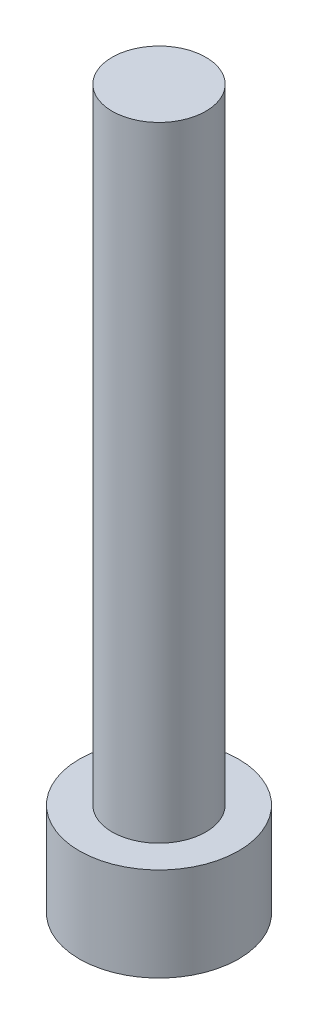
SolidWorks part; units mm, degrees
material "不锈钢 (铁素体)"
ref_plane "前视基准面" through (0, 0, 0) normal (0, 0, 1) x (1, 0, 0)
ref_plane "上视基准面" through (0, 0, 0) normal (0, 1, 0) x (1, 0, 0)
ref_plane "右视基准面" through (0, 0, 0) normal (1, 0, 0) x (0, 0, -1)
sketch "草图1" plane through (0, 0, 0) normal (0, 1, 0) x (1, 0, 0)
  circle A0 centre (0, 0) radius 5.1
  dimension "D1" = 10.2
extrude "凸台-拉伸1" add sketch "草图1" along normal blind 6
sketch "草图2" plane through (0, 6, 0) normal (0, 1, 0) x (1, 0, 0)
  circle A0 centre (0, 0) radius 3
  dimension "D1" = 6
extrude "凸台-拉伸2" add sketch "草图2" along normal blind 40
